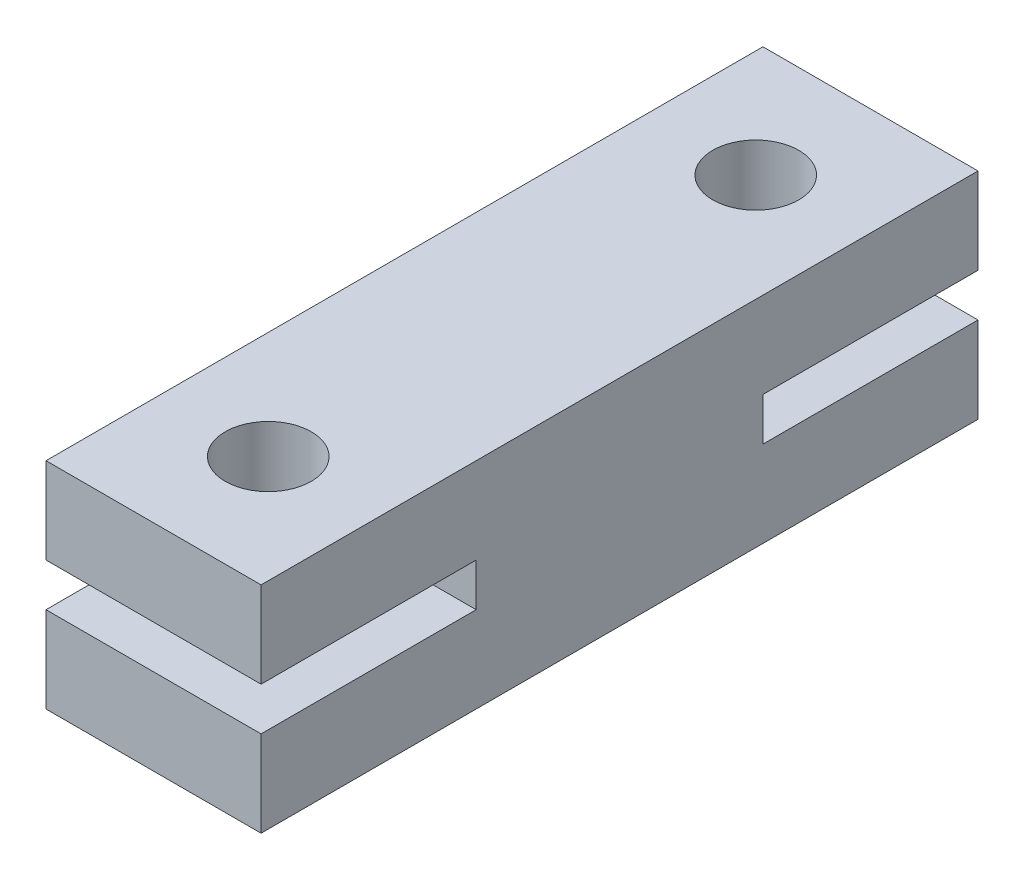
SolidWorks part; units mm, degrees
ref_plane "Plan de face" through (0, 0, 0) normal (0, 0, 1) x (1, 0, 0)
ref_plane "Plan de dessus" through (0, 0, 0) normal (0, 1, 0) x (1, 0, 0)
ref_plane "Plan de droite" through (0, 0, 0) normal (1, 0, 0) x (0, 0, -1)
sketch "Esquisse1" plane through (0, 0, 0) normal (1, 0, 0) x (0, 0, -1)
  line L1 (-25, 7.5) -> (25, 7.5)
  line L2 (-25, 7.5) -> (-25, -7.5)
  line L3 (-25, -7.5) -> (25, -7.5)
  line L4 (25, 7.5) -> (25, -7.5)
  line L5 (-25, 7.5) -> (25, -7.5) construction
  line L6 (-25, -7.5) -> (25, 7.5) construction
  point P0 (0, 0)
  dimension "D1" = 50
  dimension "D2" = 15
extrude "Boss.-Extru.1" add sketch "Esquisse1" along normal mid plane 15
sketch "Esquisse3" plane through (0, 7.5, 0) normal (0, 1, 0) x (1, 0, 0)
  line L0 (0, 0) -> (0, 17) construction
  line L1 (0, 0) -> (0, -17) construction
  circle A0 centre (0, 17) radius 3
  circle A1 centre (0, -17) radius 3
  dimension "D2" = 6
  dimension "D1" = 17
extrude "Enlèv. mat.-Extru.2" cut sketch "Esquisse3" against normal through all contours A0 | A1
sketch "Esquisse4" plane through (0, 0, 25) normal (0, 0, 1) x (1, 0, 0)
  line L0 (0, 7.5) -> (0, 1.5) construction
  line L1 (7.5, 7.5) -> (-7.5, 7.5) construction
  line L2 (0, -7.5) -> (0, -1.5) construction
  line L3 (7.5, -7.5) -> (-7.5, -7.5) construction
  line L4 (-7.5, 1.5) -> (7.5, 1.5)
  line L5 (7.5, 7.5) -> (7.5, -7.5) construction
  line L6 (-7.5, -1.5) -> (7.5, -1.5)
  line L7 (-7.5, 7.5) -> (-7.5, -7.5) construction
  line L8 (-7.5, 1.5) -> (-7.5, -1.5)
  line L9 (7.5, 1.5) -> (7.5, -1.5)
  point P14 (0, 1.5)
  point P17 (0, -1.5)
  dimension "D1" = 6
extrude "Enlèv. mat.-Extru.3" cut sketch "Esquisse4" against normal blind 15
sketch "Esquisse5" plane through (0, 0, -25) normal (0, 0, -1) x (-1, 0, 0)
  line L0 (0, 7.5) -> (0, 1.5) construction
  line L1 (-7.5, 7.5) -> (7.5, 7.5) construction
  line L2 (0, -7.5) -> (0, -1.5) construction
  line L3 (-7.5, -7.5) -> (7.5, -7.5) construction
  line L4 (-7.5, 1.5) -> (7.5, 1.5)
  line L5 (7.5, -7.5) -> (7.5, 7.5) construction
  line L6 (-7.5, -1.5) -> (7.5, -1.5)
  line L7 (-7.5, -7.5) -> (-7.5, 7.5) construction
  line L8 (-7.5, -1.5) -> (-7.5, 1.5)
  line L9 (7.5, -1.5) -> (7.5, 1.5)
  point P14 (0, 1.5)
  point P17 (0, -1.5)
  dimension "D1" = 6
extrude "Enlèv. mat.-Extru.4" cut sketch "Esquisse5" against normal blind 15
